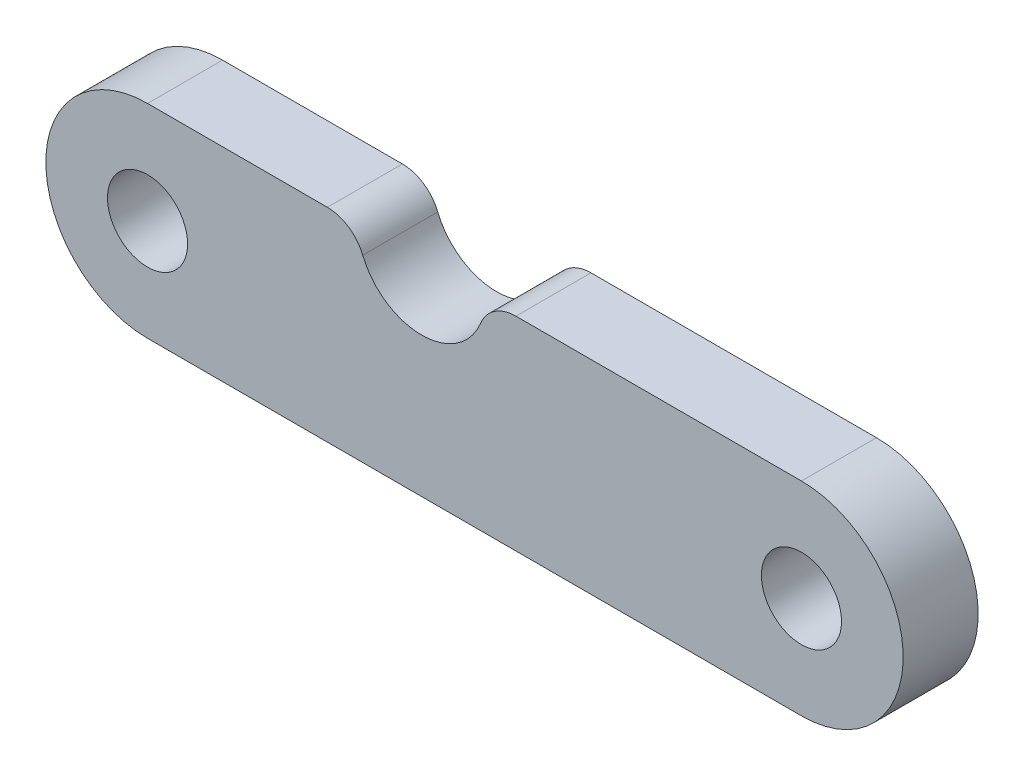
SolidWorks part; units mm, degrees
ref_plane "Front Plane" through (0, 0, 0) normal (0, 0, 1) x (1, 0, 0)
ref_plane "Top Plane" through (0, 0, 0) normal (0, 1, 0) x (1, 0, 0)
ref_plane "Right Plane" through (0, 0, 0) normal (1, 0, 0) x (0, 0, -1)
sketch "Sketch1" plane through (0, 0, 0) normal (0, 0, 1) x (1, 0, 0)
  line L0 (25.7175, 0) -> (-25.7175, 0) construction
  line L1 (25.7175, -8) -> (-25.7175, -8)
  line L2 (25.7175, 8) -> (0.8444, 8)
  line L3 (-6.1474, 8) -> (-7.2917, 8) construction
  line L4 (-9.1556, 8) -> (-25.7175, 8)
  line L5 (-0.5465, 8) -> (-2.1928, 8) construction
  line L6 (-2.1928, 8) -> (-6.1474, 8) construction
  line L7 (-7.2917, 8) -> (-9.1556, 8) construction
  line L8 (0.8444, 8) -> (-0.5465, 8) construction
  arc A0 (25.7175, -8) -> (25.7175, 8) centre (25.7175, 0) ccw
  arc A1 (-25.7175, 8) -> (-25.7175, -8) centre (-25.7175, 0) ccw
  circle A2 centre (25.7175, 0) radius 3.15
  circle A3 centre (-25.7175, 0) radius 3.15
  arc A4 (0.8444, 8) -> (-9.1556, 8) centre (-4.1556, 8) ccw construction
  circle A6 centre (-4.7422, 6.4188) radius 3 construction
  circle A7 centre (-3.347, 6.9242) radius 3 construction
  arc A8 (-9.1556, 8) -> (0.8444, 8) centre (-4.1556, 8) ccw
  point P1 (0, 0)
  point P2 (0, 0)
  point P13 (-4.7422, 8)
  point P15 (-4.1556, 8)
  dimension "D3" = 6.3
  dimension "D4" = 10
  dimension "D6" = 8
  dimension "D7" = 8
  dimension "D8" = 51.435
  dimension "D1" = 16
  dimension "D2" = 51.435
  dimension "D5" = 21.5619
extrude "Boss-Extrude1" add sketch "Sketch1" along normal blind 5.9
fillet "Fillet1" radius 3 2 edges at (0.8444, 8, 2.95) (-9.1556, 8, 2.95)
move or copy body "Body-Move/Copy1" [suppressed] bodies to move or copy 101
